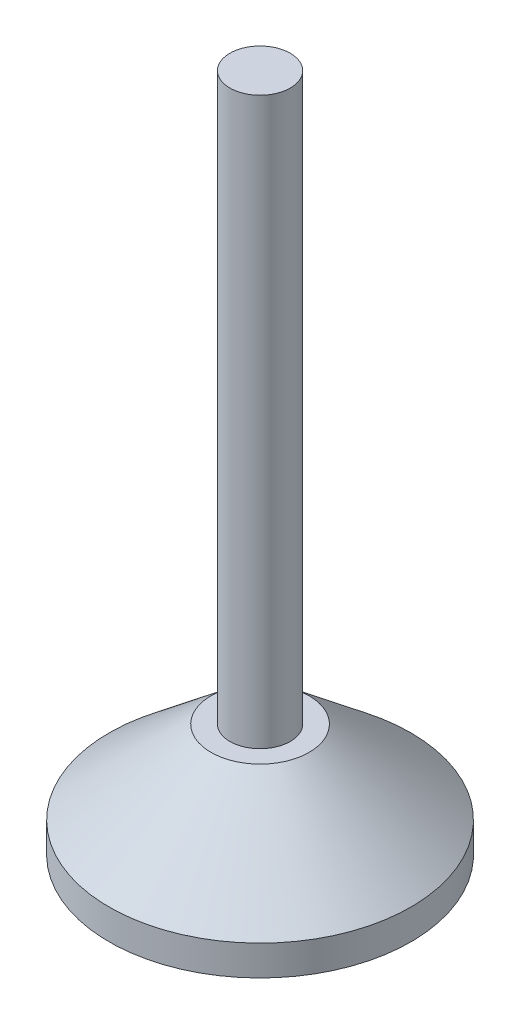
SolidWorks part; units mm, degrees
ref_plane "前视基准面" through (0, 0, 0) normal (0, 0, 1) x (1, 0, 0)
ref_plane "上视基准面" through (0, 0, 0) normal (0, 1, 0) x (1, 0, 0)
ref_plane "右视基准面" through (0, 0, 0) normal (1, 0, 0) x (0, 0, -1)
sketch "草图1" plane through (0, 0, 0) normal (0, 0, 1) x (1, 0, 0)
  line L0 (0, 0) -> (0, 180)
  line L1 (0, 180) -> (8, 180)
  line L2 (8, 180) -> (8, 30)
  line L3 (8, 30) -> (13, 30)
  line L4 (13, 30) -> (40, 8)
  line L5 (40, 8) -> (40, 0)
  line L6 (40, 0) -> (0, 0)
  point P3 (16.3155, 30)
  dimension "D1" = 8
  dimension "D2" = 40
  dimension "D3" = 8
  dimension "D4" = 150
  dimension "D5" = 30
  dimension "D6" = 5
revolve "旋转1" add sketch "草图1" angle 360 about L0
cosmetic thread "装饰螺纹线1" parameters "D1"=145, "D2"=15
